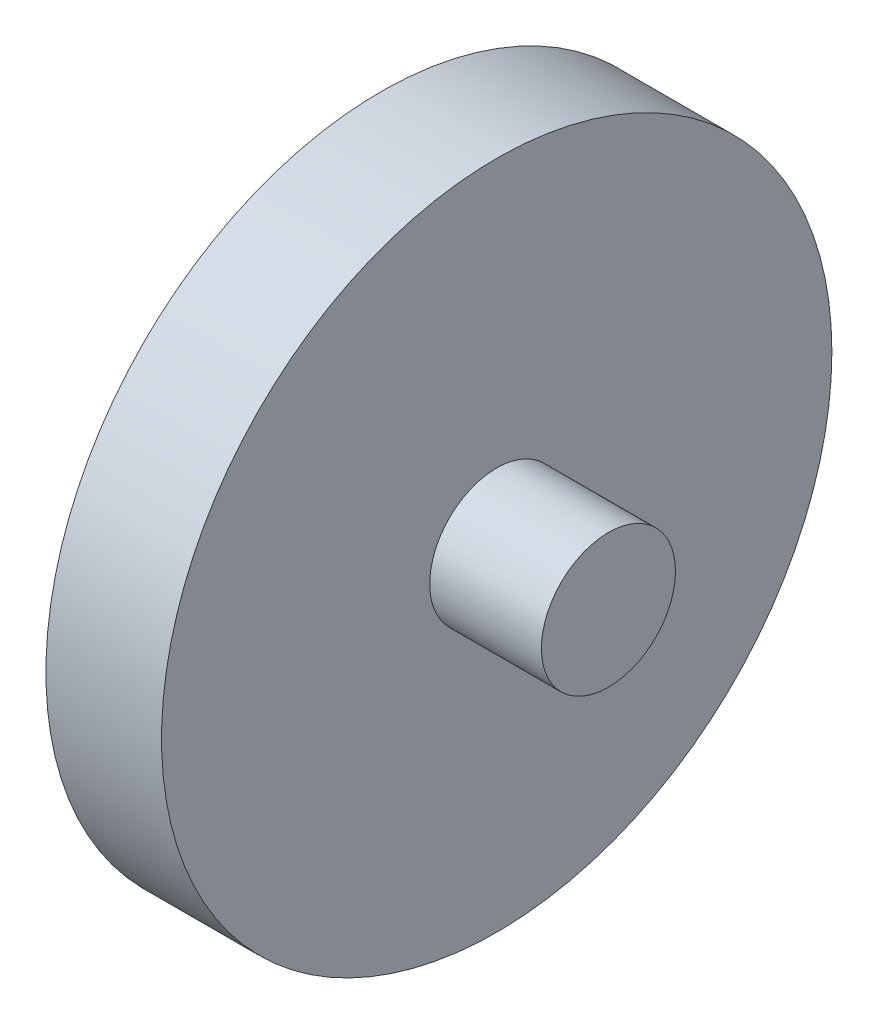
SolidWorks part; units mm, degrees
ref_plane "Front Plane" through (0, 0, 0) normal (0, 0, 1) x (1, 0, 0)
ref_plane "Top Plane" through (0, 0, 0) normal (0, 1, 0) x (1, 0, 0)
ref_plane "Right Plane" through (0, 0, 0) normal (1, 0, 0) x (0, 0, -1)
sketch "Sketch1" plane through (0, 0, 0) normal (1, 0, 0) x (0, 0, -1)
  line L0 (-15, 0) -> (15, 0) construction
  line L1 (-1.5875, 8.35) -> (1.5875, 8.35)
  line L2 (-1.5875, 8.35) -> (-1.5875, -8.35)
  line L3 (-1.5875, -8.35) -> (1.5875, -8.35)
  line L4 (1.5875, 8.35) -> (1.5875, -8.35)
  line L5 (0, -15) -> (0, 15) construction
  circle A0 centre (0, 0) radius 15
  dimension "D1" = 30
  dimension "D2" = 3.175
  dimension "D3" = 16.7
extrude "Boss-Extrude1" add sketch "Sketch1" along normal blind 4.175
sketch "Sketch2" plane through (4.175, 0, 0) normal (1, 0, 0) x (0, 0, -1)
  circle A0 centre (0, 0) radius 15 construction
  circle A1 centre (0, 0) radius 15
extrude "Boss-Extrude2" add sketch "Sketch2" along normal blind 1
sketch "Sketch3" plane through (5.175, 0, 0) normal (1, 0, 0) x (0, 0, -1)
  circle A0 centre (0, 0) radius 3
  dimension "D1" = 6
extrude "Boss-Extrude3" add sketch "Sketch3" along normal blind 5
